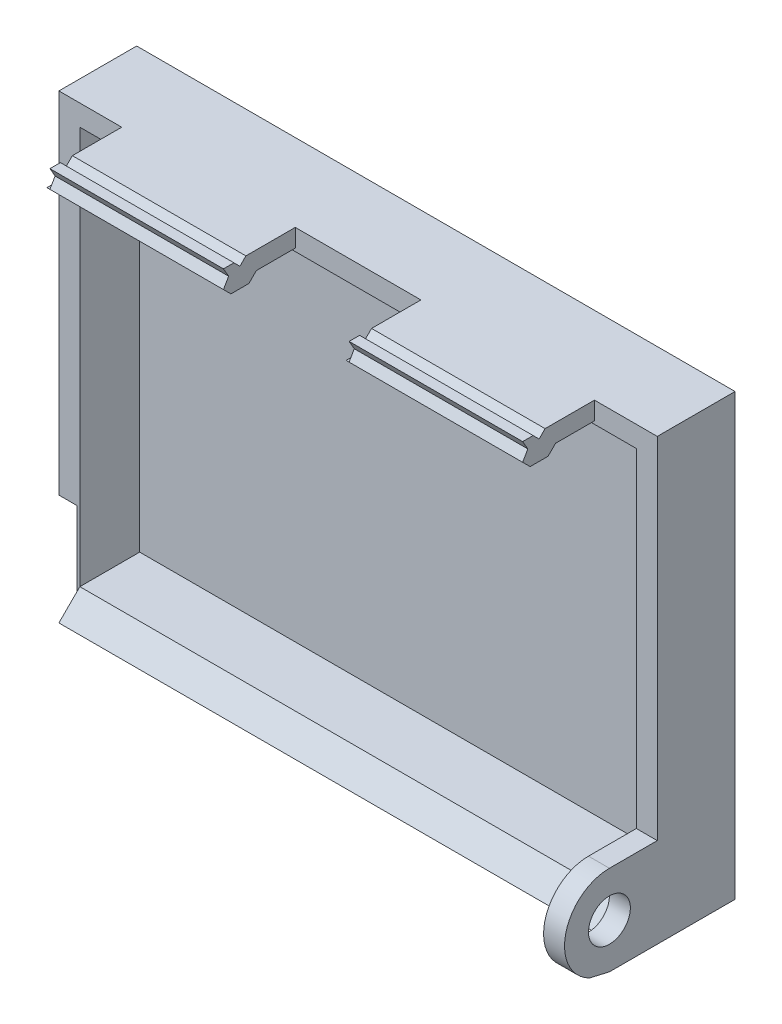
SolidWorks part; units mm, degrees
ref_plane "Front Plane" through (0, 0, 0) normal (0, 0, 1) x (1, 0, 0)
ref_plane "Top Plane" through (0, 0, 0) normal (0, 1, 0) x (1, 0, 0)
ref_plane "Right Plane" through (0, 0, 0) normal (1, 0, 0) x (0, 0, -1)
sketch "Sketch1" plane through (0, 0, 0) normal (0, 0, 1) x (1, 0, 0)
  line L1 (50, 36.75) -> (-50, 36.75)
  line L2 (50, 36.75) -> (50, -36.75)
  line L3 (50, -36.75) -> (-50, -36.75)
  line L4 (-50, 36.75) -> (-50, -36.75)
  line L5 (50, 36.75) -> (-50, -36.75) construction
  line L6 (50, -36.75) -> (-50, 36.75) construction
  line L7 (46.5, 33.25) -> (-46.5, 33.25)
  line L8 (46.5, 33.25) -> (46.5, -33.25)
  line L9 (46.5, -33.25) -> (-46.5, -33.25)
  line L10 (-46.5, 33.25) -> (-46.5, -33.25)
  line L11 (46.5, 33.25) -> (-46.5, -33.25) construction
  line L12 (46.5, -33.25) -> (-46.5, 33.25) construction
  point P0 (0, 0)
  point P6 (0, 0)
  dimension "D1" = 100
  dimension "D2" = 73.5
  dimension "D3" = 93
  dimension "D4" = 66.5
extrude "Boss-Extrude1" add sketch "Sketch1" along normal blind 10
sketch "Sketch2" plane through (0, 0, 0) normal (0, 0, -1) x (-1, 0, 0)
  line L1 (50, 36.75) -> (-50, 36.75)
  line L2 (50, 36.75) -> (50, -36.75)
  line L3 (50, -36.75) -> (-50, -36.75)
  line L4 (-50, 36.75) -> (-50, -36.75)
  line L5 (50, 36.75) -> (-50, -36.75) construction
  line L6 (50, -36.75) -> (-50, 36.75) construction
  point P0 (0, 0)
extrude "Boss-Extrude2" add sketch "Sketch2" along normal blind 3
sketch "Sketch3" plane through (50, 0, 0) normal (1, 0, 0) x (0, 0, -1)
  line L0 (-18, -29.25) -> (-18, -21.75)
  line L1 (-10, -36.75) -> (-18, -36.75)
  line L2 (-10, -36.75) -> (-10, -29.25)
  line L3 (-10, -29.25) -> (-18, -29.25)
  line L4 (-18, -36.75) -> (-18, -29.25)
  line L5 (-18, -21.75) -> (-10, -21.75)
  line L6 (-10, -36.75) -> (-10, 36.75) construction
  line L7 (-18, -29.25) -> (-25.5, -29.25)
  line L8 (-25.5, -29.25) -> (-25.5, -35)
  line L9 (-25.5, -35) -> (-18, -36.75)
  line L10 (-18, -36.75) -> (-25.5, -35)
  circle A0 centre (-18, -29.25) radius 7.5
  circle A1 centre (-18, -29.25) radius 3.5
  line M6 (-10, 36.75) -> (-10, -36.75)
  dimension "D3" = 15
  dimension "D4" = 7
  dimension "D1" = 8
  dimension "D2" = 7.5
extrude "Boss-Extrude8" add sketch "Sketch3" against normal blind 3.5 contours A1 L7 A0 L4 | A1 L4 A0 L3 | A0 L1 L3 M6 | A0 L3 L5 M6 | A1 L3 A0 L0 | A1 L0 A0 L7
sketch "Sketch4" plane through (-50, 0, 0) normal (-1, 0, 0) x (0, 0, 1)
  line L12 (10, -36.75) -> (-2, -36.75)
  line L13 (10, -36.75) -> (10, -21.75)
  line L14 (10, -21.75) -> (-2, -21.75)
  line L15 (-2, -36.75) -> (-2, -21.75)
  dimension "D1" = 12
  dimension "D2" = 15
extrude "Cut-Extrude4" cut sketch "Sketch4" against normal blind 3
sketch "Sketch7" plane through (0, 0, 10) normal (0, 0, 1) x (1, 0, 0)
  line L0 (50, 33.75) -> (-50, 33.75) construction
  line L1 (50, -21.75) -> (50, 36.75) construction
  line L2 (-50, 36.75) -> (-50, -21.75) construction
  line L4 (-50, 36.75) -> (50, 36.75)
  line L5 (-50, 36.75) -> (-50, 33.75)
  line L6 (-50, 33.75) -> (50, 33.75)
  line L7 (50, 36.75) -> (50, 33.75)
  dimension "D1" = 3
extrude "Boss-Extrude12" add sketch "Sketch7" along normal blind 12
sketch "Sketch8" plane through (0, 0, 22) normal (0, 0, 1) x (1, 0, 0)
  line L0 (-50, 33.75) -> (50, 33.75) construction
  line L1 (-50, 36.75) -> (-39.5, 36.75)
  line L2 (-50, 36.75) -> (-50, 33.75)
  line L3 (-50, 33.75) -> (-39.5, 33.75)
  line L4 (-39.5, 36.75) -> (-39.5, 33.75)
  line L6 (50, 36.75) -> (39.5, 36.75)
  line L7 (50, 36.75) -> (50, 33.75)
  line L8 (50, 33.75) -> (39.5, 33.75)
  line L9 (39.5, 36.75) -> (39.5, 33.75)
  line L10 (-39.5, 36.75) -> (-10.5, 36.75)
  line L11 (-39.5, 36.75) -> (-39.5, 33.75)
  line L12 (-39.5, 33.75) -> (-10.5, 33.75)
  line L13 (-10.5, 36.75) -> (-10.5, 33.75)
  line L14 (39.5, 36.75) -> (10.5, 36.75)
  line L15 (39.5, 36.75) -> (39.5, 33.75)
  line L16 (39.5, 33.75) -> (10.5, 33.75)
  line L17 (10.5, 36.75) -> (10.5, 33.75)
  line L18 (10.5, 33.75) -> (-10.5, 33.75)
  line L19 (10.5, 33.75) -> (10.5, 36.75)
  line L20 (10.5, 36.75) -> (-10.5, 36.75)
  line L21 (-10.5, 33.75) -> (-10.5, 36.75)
  line M5 (50, 33.75) -> (50, 36.75)
  line M6 (50, 36.75) -> (-50, 36.75)
  line M7 (-50, 36.75) -> (-50, 33.75)
  line M8 (-50, 33.75) -> (50, 33.75)
  dimension "D1" = 10.5
  dimension "D2" = 10.5
  dimension "D3" = 29
  dimension "D4" = 29
extrude "Cut-Extrude2" cut sketch "Sketch8" against normal blind 12 contours L17 L13 M6 M8 | L4 M6 M7 M8 | L9 M6 M8 M5
sketch "Sketch9" plane through (39.5, 0, 0) normal (1, 0, 0) x (0, 0, -1)
  line L5 (-10, 33.75) -> (-22, 33.75) construction
  line L6 (-22, 33.75) -> (-20.75, 32.5)
  line L7 (-20.75, 32.5) -> (-17.75, 32.5)
  line L8 (-17.75, 32.5) -> (-16.5, 33.75)
  line L9 (-16.5, 33.75) -> (-22, 33.75)
  dimension "D1" = 1.25
  dimension "D5" = 45
  dimension "D6" = 45
  dimension "D7" = 5.5
  dimension "D8" = 3
extrude "Boss-Extrude13" add sketch "Sketch9" against normal blind 29.5
sketch "Sketch10" plane through (-10.5, 0, 0) normal (1, 0, 0) x (0, 0, -1)
  line L4 (-22, 33.75) -> (-20.75, 32.5)
  line L5 (-22, 33.75) -> (-20.75, 32.5)
  line L6 (-20.75, 32.5) -> (-17.75, 32.5)
  line L7 (-20.75, 32.5) -> (-17.75, 32.5)
  line L12 (-17.75, 32.5) -> (-16.5, 33.75)
  line L13 (-17.75, 32.5) -> (-16.5, 33.75)
  line L14 (-16.5, 33.75) -> (-22, 33.75)
  line L15 (-16.5, 33.75) -> (-22, 33.75)
  dimension "D1" = 0
extrude "Boss-Extrude14" add sketch "Sketch10" against normal blind 29.5
sketch "Sketch11" plane through (39.5, 0, 0) normal (1, 0, 0) x (0, 0, -1)
  line L0 (-20.25, 36.75) -> (-19.25, 35.75)
  line L1 (-10, 36.75) -> (-22, 36.75) construction
  line L2 (-19.25, 35.75) -> (-18.25, 36.75)
  line L3 (-18.25, 36.75) -> (-20.25, 36.75)
  line L4 (-19.25, 36.75) -> (-19.25, 35.75)
  line L5 (-22, 36.75) -> (-21.134, 35.25)
  line L6 (-21.134, 35.25) -> (-22, 33.75)
  line L7 (-22, 33.75) -> (-22, 36.75)
  line L8 (-21.134, 35.25) -> (-22, 35.25)
  line M9 (-22, 36.75) -> (-22, 33.75)
  line M15 (-10, 36.75) -> (-22, 36.75)
  dimension "D1" = 2.75
  dimension "D2" = 45
  dimension "D3" = 2
  dimension "D4" = 30
  dimension "D5" = 30
extrude "Cut-Extrude3" cut sketch "Sketch11" against normal blind 93.5 contours L4 L2 M15 | L4 L3 L0 | L8 L5 M9 | L6 L8 L7
sketch "Sketch12" plane through (46.5, 0, 0) normal (-1, 0, 0) x (0, 0, 1)
  line L0 (10, -36.75) -> (13.5, -36.75)
  line L1 (10, -36.75) -> (18, -36.75) construction
  line L2 (13.5, -36.75) -> (10, -33.25)
  line L3 (10, -33.25) -> (10, -36.75)
  dimension "D1" = 3.5
extrude "Boss-Extrude15" add sketch "Sketch12" along normal blind 93
